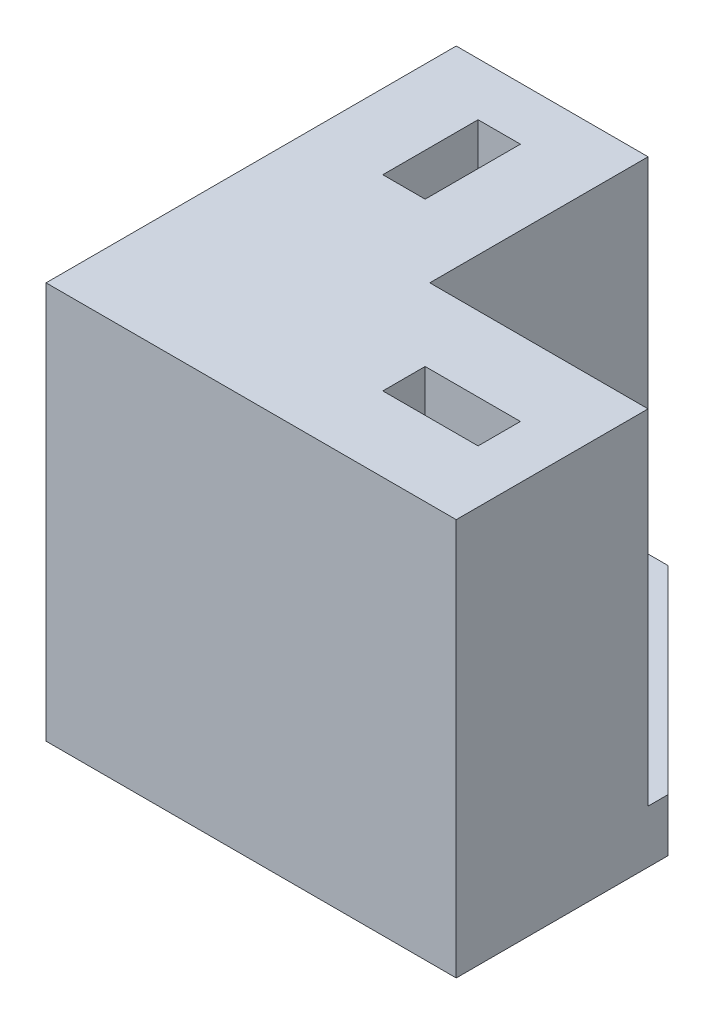
SolidWorks part; units mm, degrees
ref_plane "Front Plane" through (0, 0, 0) normal (0, 0, 1) x (1, 0, 0)
ref_plane "Top Plane" through (0, 0, 0) normal (0, 1, 0) x (1, 0, 0)
ref_plane "Right Plane" through (0, 0, 0) normal (1, 0, 0) x (0, 0, -1)
sketch "Sketch3" plane through (0, 0, 0) normal (0, 1, 0) x (1, 0, 0)
  line L1 (-9.8425, -9.8425) -> (9.8425, -9.8425)
  line L2 (-9.8425, -9.8425) -> (-9.8425, 9.8425)
  line L3 (-9.8425, 9.8425) -> (9.8425, 9.8425)
  line L4 (9.8425, -9.8425) -> (9.8425, 9.8425)
  line L5 (-9.8425, -9.8425) -> (9.8425, 9.8425) construction
  line L6 (-9.8425, 9.8425) -> (9.8425, -9.8425) construction
  point P0 (0, 0)
  dimension "D1" = 19.685
  dimension "D2" = 19.685
extrude "Boss-Extrude2" add sketch "Sketch3" along normal blind 19.05
sketch "Sketch4" plane through (0, 19.05, 0) normal (0, 1, 0) x (1, 0, 0)
  line L0 (9.8425, 9.8425) -> (0, 9.8425)
  line L1 (9.8425, 9.8425) -> (-9.8425, 9.8425) construction
  line L2 (0, 9.8425) -> (0, 0)
  line L3 (0, 0) -> (9.8425, 0)
  line L4 (9.8425, -9.8425) -> (9.8425, 9.8425) construction
  line L5 (9.8425, 0) -> (9.8425, 9.8425)
sketch "Sketch5" plane through (0, 0, 0) normal (0, -1, 0) x (1, 0, 0)
  line L1 (0, 0) -> (-9.8425, 9.8425) construction
  circle A1 centre (-4.9212, 4.9213) radius 2.54
  dimension "D1" = 5.08
extrude "Cut-Extrude2" cut sketch "Sketch5" against normal blind 5.715
sketch "Sketch6" plane through (0, 19.05, 0) normal (0, 1, 0) x (1, 0, 0)
  line L0 (9.8425, -0.635) -> (-0.635, -0.635)
  line L1 (9.8425, -9.8425) -> (9.8425, 9.8425) construction
  line L2 (-0.635, -0.635) -> (-0.635, 9.8425)
  line L3 (9.8425, 9.8425) -> (-9.8425, 9.8425) construction
  line L4 (9.8425, 9.8425) -> (0, 9.8425) construction
  line L5 (-0.635, 9.8425) -> (9.8425, 9.8425)
  line L6 (9.8425, 9.8425) -> (9.8425, -0.635)
  dimension "D1" = 10.4775
  dimension "D2" = 10.4775
extrude "Cut-Extrude3" cut sketch "Sketch6" against normal blind 16.51
sketch "Sketch7" plane through (0, 19.05, 0) normal (0, 1, 0) x (1, 0, 0)
  line L0 (-5.2387, 9.8425) -> (-5.2387, -9.8425) construction
  line L1 (-0.635, 9.8425) -> (-9.8425, 9.8425) construction
  line L2 (-9.8425, -9.8425) -> (9.8425, -9.8425) construction
  line L3 (9.8425, -5.2387) -> (-9.8425, -5.2388) construction
  line L4 (9.8425, -9.8425) -> (9.8425, -0.635) construction
  line L5 (-9.8425, 9.8425) -> (-9.8425, -9.8425) construction
  line L7 (-6.2547, 2.7305) -> (-4.2227, 2.7305)
  line L8 (-6.2547, 2.7305) -> (-6.2547, 7.3025)
  line L9 (-6.2547, 7.3025) -> (-4.2227, 7.3025)
  line L10 (-4.2227, 2.7305) -> (-4.2227, 7.3025)
  line L11 (-6.2547, 2.7305) -> (-4.2227, 7.3025) construction
  line L12 (-6.2547, 7.3025) -> (-4.2227, 2.7305) construction
  line L13 (2.7305, -6.2547) -> (7.3025, -6.2547)
  line L14 (2.7305, -6.2547) -> (2.7305, -4.2227)
  line L15 (2.7305, -4.2227) -> (7.3025, -4.2227)
  line L16 (7.3025, -6.2547) -> (7.3025, -4.2227)
  line L17 (2.7305, -6.2547) -> (7.3025, -4.2227) construction
  line L18 (2.7305, -4.2227) -> (7.3025, -6.2547) construction
  point P12 (-5.2387, 5.0165)
  point P17 (5.0165, -5.2388)
  dimension "D1" = 2.032
  dimension "D2" = 4.572
  dimension "D3" = 2.54
  dimension "D6" = 2.54
extrude "Cut-Extrude4" cut sketch "Sketch7" against normal blind 5.08
chamfer "Chamfer1" distance 9.525 angle 45 1 edges at (9.8425, 1.27, -9.8425)
